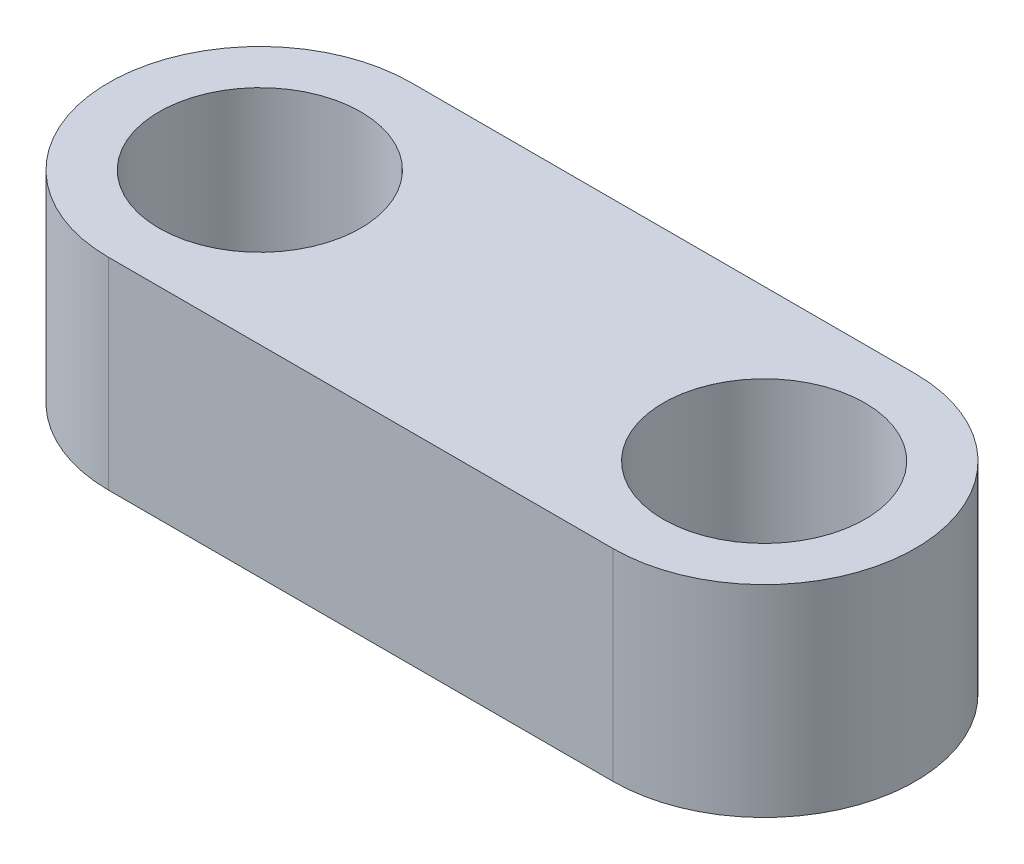
SolidWorks part; units mm, degrees
ref_plane "Front Plane" through (0, 0, 0) normal (0, 0, 1) x (1, 0, 0)
ref_plane "Top Plane" through (0, 0, 0) normal (0, 1, 0) x (1, 0, 0)
ref_plane "Right Plane" through (0, 0, 0) normal (1, 0, 0) x (0, 0, -1)
sketch "Sketch1" plane through (0, 0, 0) normal (0, 1, 0) x (1, 0, 0)
  line L0 (0, 0) -> (25, 0)
  line L1 (0, 0) -> (0, 15) construction
  line L2 (0, 15) -> (25, 15)
  line L3 (25, 0) -> (25, 15) construction
  arc A0 (0, 15) -> (0, 0) centre (0, 7.5) ccw
  arc A1 (25, 0) -> (25, 15) centre (25, 7.5) ccw
  circle A2 centre (0, 7.5) radius 5
  circle A3 centre (25, 7.5) radius 5
  dimension "D3" = 10
  dimension "D4" = 10
  dimension "D1" = 25
  dimension "D2" = 15
extrude "Boss-Extrude1" add sketch "Sketch1" along normal blind 10
